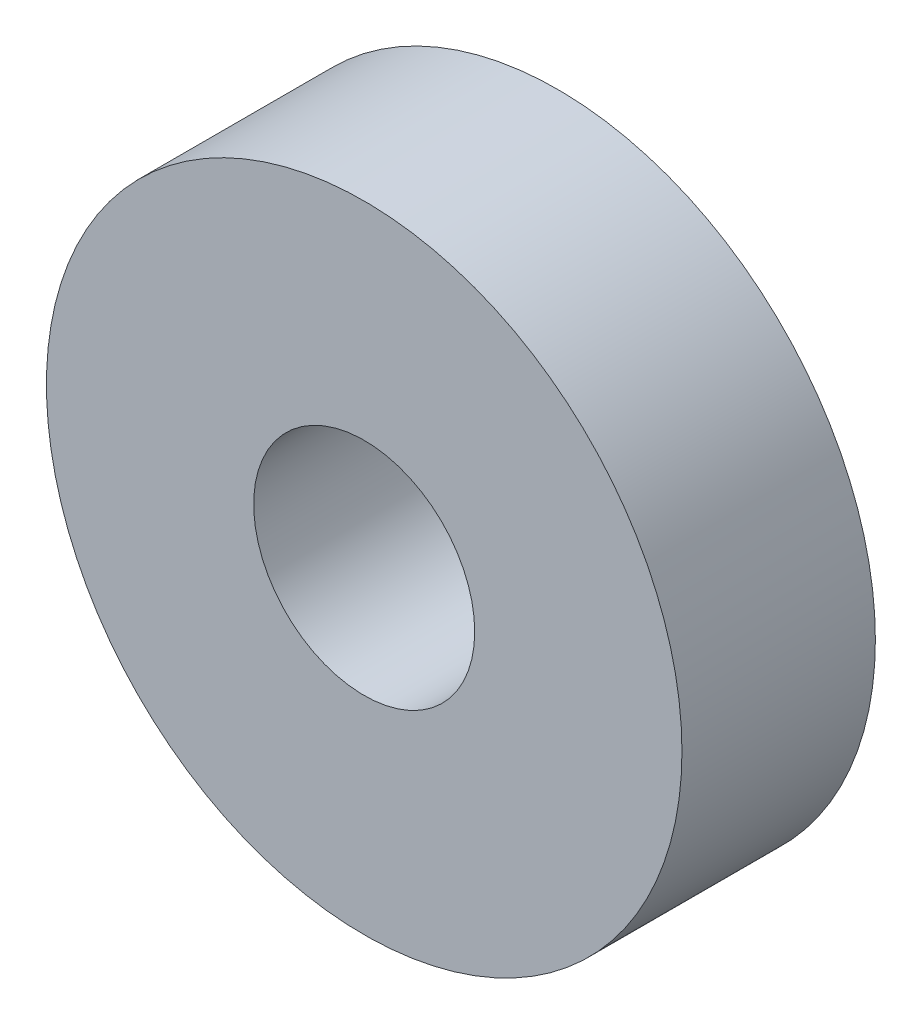
SolidWorks part; units mm, degrees
material "PTFE (general)"
ref_plane "Front Plane" through (0, 0, 0) normal (0, 0, 1) x (1, 0, 0)
ref_plane "Top Plane" through (0, 0, 0) normal (0, 1, 0) x (1, 0, 0)
ref_plane "Right Plane" through (0, 0, 0) normal (1, 0, 0) x (0, 0, -1)
sketch "Sketch1" plane through (0, 0, 0) normal (0, 0, 1) x (1, 0, 0)
  circle A0 centre (0, 0) radius 11.5
  circle A1 centre (0, 0) radius 4
  dimension "D1" = 8
  dimension "D2" = 23
extrude "Boss-Extrude1" add sketch "Sketch1" along normal blind 7
